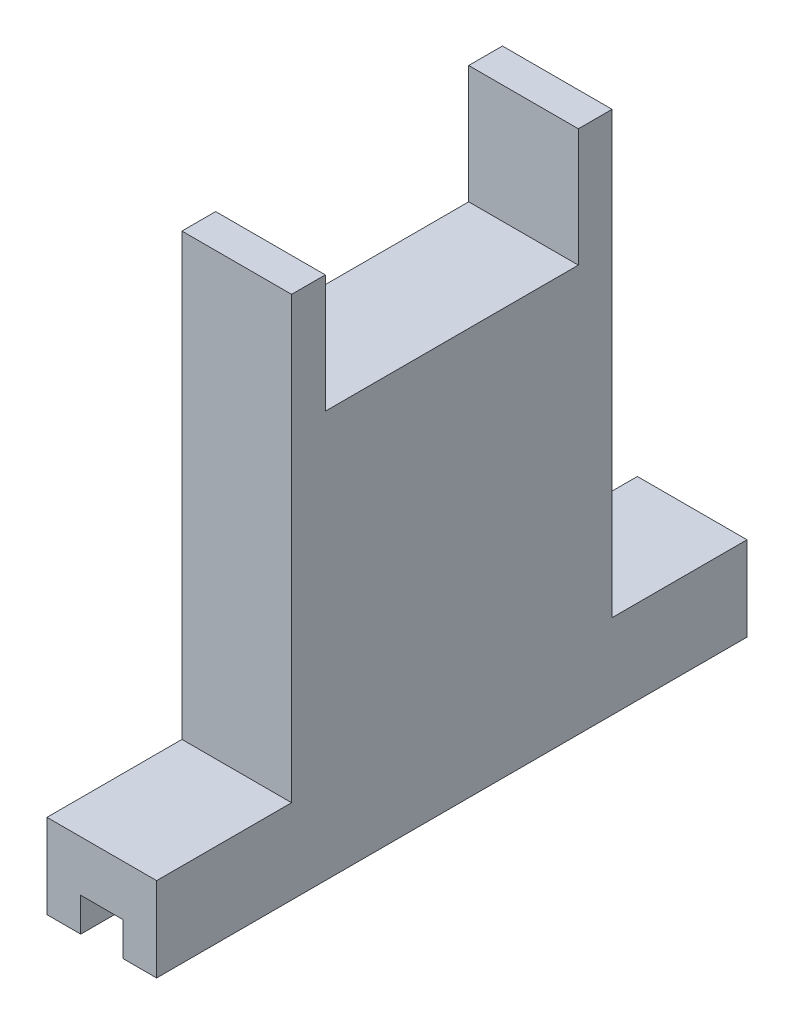
SolidWorks part; units mm, degrees
ref_plane "Front" through (0, 0, 0) normal (0, 0, 1) x (1, 0, 0)
ref_plane "Top" through (0, 0, 0) normal (0, 1, 0) x (1, 0, 0)
ref_plane "Right" through (0, 0, 0) normal (1, 0, 0) x (0, 0, -1)
sketch "Эскиз2" plane through (0, 0, 0) normal (0, 1, 0) x (1, 0, 0)
  line L1 (-89.9179, 39.016) -> (-83.4179, 39.016)
  line L2 (-89.9179, 39.016) -> (-89.9179, 4.016)
  line L3 (-89.9179, 4.016) -> (-83.4179, 4.016)
  line L4 (-83.4179, 39.016) -> (-83.4179, 4.016)
  dimension "D1" = 35
  dimension "D2" = 6.5
extrude "Бобышка-Вытянуть1" add sketch "Эскиз2" along normal blind 5
sketch "Эскиз3" plane through (0, 0, -4.016) normal (0, 0, 1) x (1, 0, 0)
  line L0 (-89.9179, 0) -> (-83.4179, 0) construction
  line L1 (-85.4179, 0) -> (-87.9179, 0)
  line L2 (-85.4179, 0) -> (-85.4179, 2)
  line L3 (-85.4179, 2) -> (-87.9179, 2)
  line L4 (-87.9179, 0) -> (-87.9179, 2)
  line L5 (-89.9179, 5) -> (-89.9179, 0) construction
  dimension "D1" = 2.5
  dimension "D2" = 2
  dimension "D3" = 2
extrude "Вырез-Вытянуть1" cut sketch "Эскиз3" against normal blind 180
sketch "Эскиз4" plane through (0, 5, 0) normal (0, 1, 0) x (1, 0, 0)
  line L0 (-89.9179, 39.016) -> (-89.9179, 4.016) construction
  line L1 (-89.9179, 31.016) -> (-83.4179, 31.016)
  line L2 (-89.9179, 31.016) -> (-89.9179, 12.016)
  line L3 (-89.9179, 12.016) -> (-83.4179, 12.016)
  line L4 (-83.4179, 31.016) -> (-83.4179, 12.016)
  line L5 (-83.4179, 4.016) -> (-83.4179, 39.016) construction
  line L6 (-83.4179, 39.016) -> (-89.9179, 39.016) construction
  dimension "D1" = 19
  dimension "D2" = 8
extrude "Бобышка-Вытянуть2" add sketch "Эскиз4" along normal blind 26.1
sketch "Эскиз5" plane through (0, 31.1, 0) normal (0, 1, 0) x (1, 0, 0)
  line L0 (-83.4179, 12.016) -> (-83.4179, 31.016) construction
  line L1 (-83.4179, 29.016) -> (-89.9179, 29.016)
  line L2 (-83.4179, 29.016) -> (-83.4179, 14.016)
  line L3 (-83.4179, 14.016) -> (-89.9179, 14.016)
  line L4 (-89.9179, 29.016) -> (-89.9179, 14.016)
  line L5 (-89.9179, 31.016) -> (-89.9179, 12.016) construction
  line L6 (-83.4179, 31.016) -> (-89.9179, 31.016) construction
  dimension "D1" = 15
  dimension "D2" = 2
extrude "Вырез-Вытянуть2" cut sketch "Эскиз5" against normal blind 7
